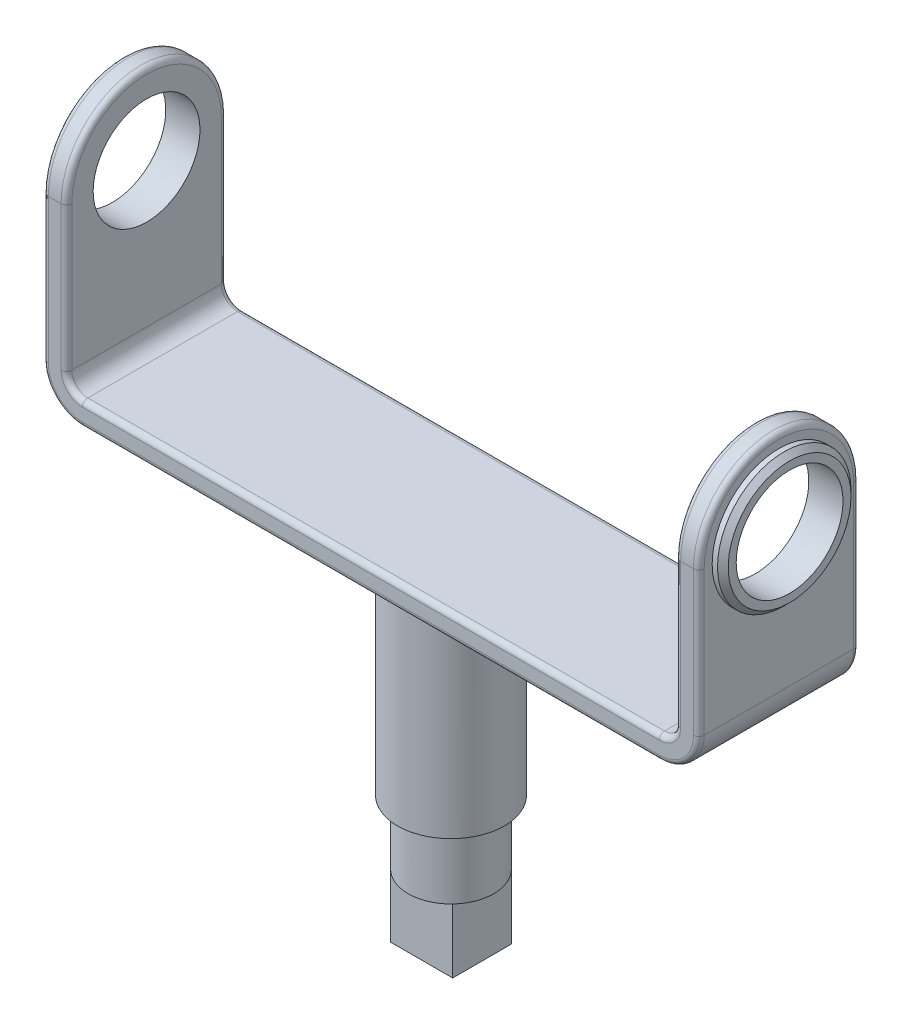
SolidWorks part; units mm, degrees
ref_plane "Front Plane" through (0, 0, 0) normal (0, 0, 1) x (1, 0, 0)
ref_plane "Top Plane" through (0, 0, 0) normal (0, 1, 0) x (1, 0, 0)
ref_plane "Right Plane" through (0, 0, 0) normal (1, 0, 0) x (0, 0, -1)
sketch "Sketch1" plane through (0, 0, 0) normal (0, 0, 1) x (1, 0, 0)
  line L0 (0, 0) -> (0, 15)
  line L1 (0, 0) -> (57, 0)
  line L2 (57, 0) -> (57, 15)
  dimension "D1" = 57
  dimension "D2" = 15
extrude "Extrude-Thin1" add sketch "Sketch1" along normal mid plane 15 thin thin type one direction wall 2.2
sketch "Sketch2" plane through (59.2, 0, 0) normal (1, 0, 0) x (0, 0, -1)
  line L0 (-7.5, 15) -> (7.5, 15) construction
  line L6 (7.5, 1.5) -> (7.5, 15)
  line L7 (7.5, 15) -> (-7.5, 15)
  line L8 (-7.5, 15) -> (-7.5, 1.5)
  line L9 (-7.5, 1.5) -> (7.5, 1.5)
  line L10 (7.5, 1.5) -> (7.5, 15)
  line L12 (-7.5, 15) -> (-7.5, 1.5)
  line L13 (-7.5, 1.5) -> (7.5, 1.5)
  arc A0 (7.5, 15) -> (-7.5, 15) centre (0, 15) ccw
  dimension "D1" = 0
extrude "Boss-Extrude4" add sketch "Sketch2" against normal blind 2.2 contours A0 L12 L13 L10
sketch "Sketch3" plane through (-2.2, 0, 0) normal (-1, 0, 0) x (0, 0, 1)
  line L0 (7.5, 15) -> (-7.5, 15) construction
  line L6 (-7.5, 15) -> (-7.5, 1.5)
  line L7 (-7.5, 1.5) -> (7.5, 1.5)
  line L8 (7.5, 1.5) -> (7.5, 15)
  line L9 (7.5, 15) -> (-7.5, 15)
  line L13 (7.5, 15) -> (-7.5, 15)
  arc A0 (7.5, 15) -> (-7.5, 15) centre (0, 15) ccw
  dimension "D1" = 0
extrude "Boss-Extrude5" add sketch "Sketch3" against normal blind 2.2
sketch "Sketch4" plane through (-2.2, 0, 0) normal (-1, 0, 0) x (0, 0, 1)
  circle A0 centre (0, 15) radius 5
  dimension "D1" = 10
extrude "Cut-Extrude1" cut sketch "Sketch4" against normal through all both and the other way through all
sketch "Sketch5" plane through (0, -2.2, 0) normal (0, -1, 0) x (1, 0, 0)
  circle A0 centre (28.5, 0) radius 5
  dimension "D2" = 10
  dimension "D1" = 28.5
extrude "Boss-Extrude6" add sketch "Sketch5" along normal blind 20
sketch "Sketch6" plane through (0, -22.2, 0) normal (0, -1, 0) x (1, 0, 0)
  circle A0 centre (28.5, 0) radius 4
  dimension "D1" = 8
extrude "Boss-Extrude7" add sketch "Sketch6" along normal blind 6
sketch "Sketch7" plane through (0, -28.2, 0) normal (0, -1, 0) x (1, 0, 0)
  line L1 (25.5953, 2.75) -> (31.4047, 2.75)
  line L2 (25.5953, 2.75) -> (25.5953, -2.75)
  line L3 (25.5953, -2.75) -> (31.4047, -2.75)
  line L4 (31.4047, 2.75) -> (31.4047, -2.75)
  line L5 (25.5953, 2.75) -> (31.4047, -2.75) construction
  line L6 (25.5953, -2.75) -> (31.4047, 2.75) construction
  circle A0 centre (28.5, 0) radius 4 construction
  point P0 (28.5, 0)
  dimension "D1" = 5.5
extrude "Boss-Extrude8" add sketch "Sketch7" along normal blind 6
sketch "Sketch8" plane through (-2.2, 0, 0) normal (-1, 0, 0) x (0, 0, 1)
  circle A0 centre (0, 15) radius 6.25
  circle A1 centre (0, 15) radius 5
  dimension "D1" = 12.5
  dimension "D2" = 10
extrude "Boss-Extrude11" add sketch "Sketch8" along normal blind 1 contours A0 | A1
sketch "Sketch9" plane through (59.2, 0, 0) normal (1, 0, 0) x (0, 0, -1)
  circle A0 centre (0, 15) radius 6.25
  circle A1 centre (0, 15) radius 5
  dimension "D1" = 12.5
  dimension "D2" = 10
extrude "Boss-Extrude12" add sketch "Sketch9" along normal blind 1
chamfer "Chamfer2" distance 0.5 angle 45 1 edges at (60.2, 15, -6.25)
chamfer "Chamfer3" distance 0.5 angle 45 1 edges at (-3.2, 15, 6.25)
fillet "Fillet1" radius 0.5 24 edges at (-1.1163, -1.1163, 7.5) (-2.2, 8.25, 7.5) (-2.2, 22.5, 0) (0, 22.5, 0) (-2.2, 8.25, -7.5) (-1.1163, -1.1163, -7.5) (28.5, -2.2, -7.5) (58.1163, -1.1163, -7.5) (59.2, 8.25, -7.5) (59.2, 22.5, 0) (57, 22.5, 0) (59.2, 8.25, 7.5) (58.1163, -1.1163, 7.5) (0.4393, 0.4393, 7.5) (0, 8.25, 7.5) (0, 8.25, -7.5) (0.4393, 0.4393, -7.5) (28.5, 0, -7.5) (56.5607, 0.4393, -7.5) (57, 8.25, -7.5) (57, 8.25, 7.5) (56.5607, 0.4393, 7.5) (28.5, -2.2, 7.5) (28.5, 0, 7.5)
